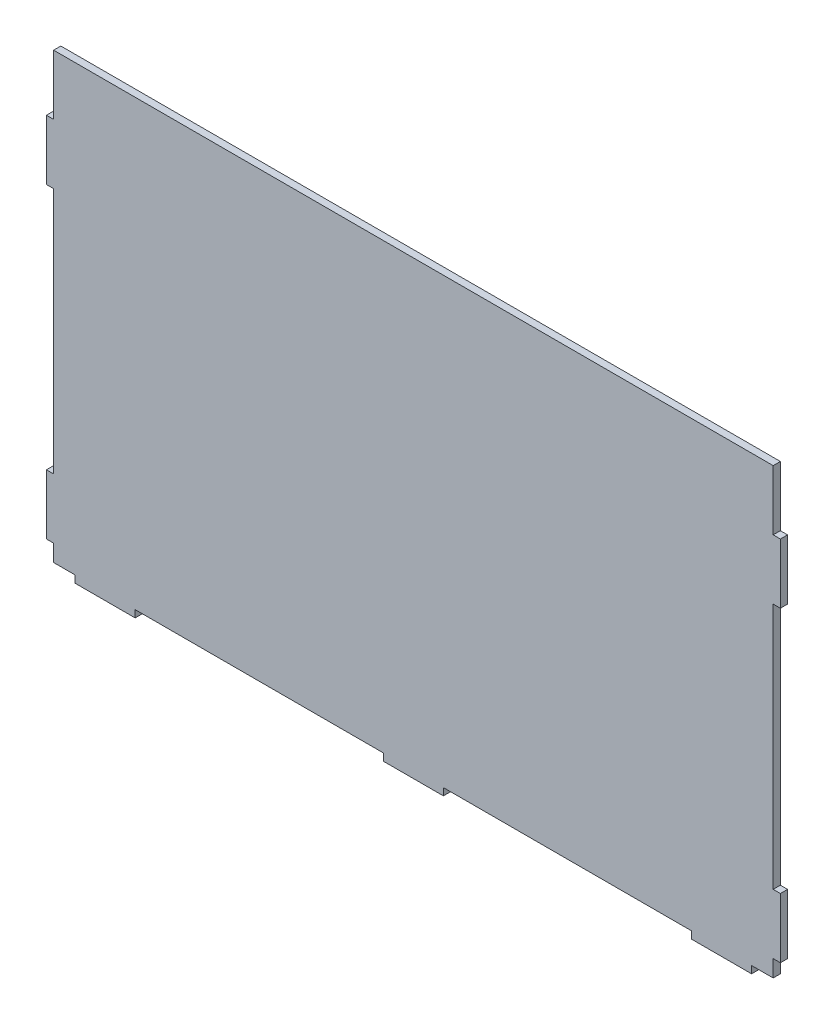
SolidWorks part; units mm, degrees
material "Maple"
ref_plane "Front Plane" through (0, 0, 0) normal (0, 0, 1) x (1, 0, 0)
ref_plane "Top Plane" through (0, 0, 0) normal (0, 1, 0) x (1, 0, 0)
ref_plane "Right Plane" through (0, 0, 0) normal (1, 0, 0) x (0, 0, -1)
sketch "Sketch1" plane through (0, 0, 0) normal (0, 0, 1) x (1, 0, 0)
  line L0 (128.9646, -1027.1029) -> (128.9646, -1021.1029)
  line L13 (146.9646, -651.1029) -> (-453.0354, -651.1029)
  line L59 (-453.0354, -651.1029) -> (-453.0354, -701.1029)
  line L60 (-453.0354, -701.1029) -> (-459.0354, -701.1029)
  line L61 (-459.0354, -701.1029) -> (-459.0354, -751.1029)
  line L62 (-459.0354, -751.1029) -> (-453.0354, -751.1029)
  line L63 (-453.0354, -751.1029) -> (-453.0354, -957.1029)
  line L64 (128.9646, -1021.1029) -> (146.9646, -1021.1029)
  line L71 (152.9646, -1007.1029) -> (152.9646, -957.1029)
  line L76 (-459.0354, -957.1029) -> (-453.0354, -957.1029)
  line L77 (-459.0354, -1007.1029) -> (-459.0354, -957.1029)
  line L78 (-453.0354, -1007.1029) -> (-459.0354, -1007.1029)
  line L79 (-453.0354, -1021.1029) -> (-453.0354, -1007.1029)
  line L81 (128.9646, -1027.1029) -> (78.9646, -1027.1029)
  line L83 (-435.0354, -1021.1029) -> (-435.0354, -1027.1029)
  line L84 (-435.0354, -1027.1029) -> (-385.0354, -1027.1029)
  line L85 (-385.0354, -1021.1029) -> (-385.0354, -1027.1029)
  line L86 (78.9646, -1021.1029) -> (-128.0354, -1021.1029)
  line L87 (-178.0354, -1021.1029) -> (-385.0354, -1021.1029)
  line L88 (78.9646, -1021.1029) -> (78.9646, -1027.1029)
  line L91 (-435.0354, -1021.1029) -> (-453.0354, -1021.1029)
  line L93 (-178.0354, -1021.1029) -> (-178.0354, -1027.1029)
  line L94 (-178.0354, -1027.1029) -> (-128.0354, -1027.1029)
  line L95 (-128.0354, -1021.1029) -> (-128.0354, -1027.1029)
  line L96 (152.9646, -957.1029) -> (146.9646, -957.1029)
  line L97 (146.9646, -751.1029) -> (146.9646, -957.1029)
  line L98 (152.9646, -751.1029) -> (146.9646, -751.1029)
  line L99 (152.9646, -701.1029) -> (152.9646, -751.1029)
  line L100 (146.9646, -701.1029) -> (152.9646, -701.1029)
  line L101 (146.9646, -651.1029) -> (146.9646, -701.1029)
  line L102 (146.9646, -1021.1029) -> (146.9646, -1007.1029)
  line L103 (146.9646, -1007.1029) -> (152.9646, -1007.1029)
  point P0 (137.9646, -1021.1029)
  point P18 (-456.0354, -751.1029)
  point P19 (146.9646, -1014.1029)
  point P21 (78.9646, -1024.1029)
  point P23 (146.1763, -615.6029)
  dimension "D2" = 50
  dimension "D3" = 6
  dimension "D4" = 50
  dimension "D5" = 6
  dimension "D6" = 14
  dimension "D7" = 50
  dimension "D8" = 18
  dimension "D9" = 50
  dimension "D10" = 50
  dimension "D11" = 370
  dimension "D12" = 50
  dimension "D13" = 6
  dimension "D14" = 14
  dimension "D15" = 50
  dimension "D16" = 600
  dimension "D17" = 370
  dimension "D18" = 600
  dimension "D19" = 600
  dimension "D20" = 6
  dimension "D21" = 6
  dimension "D22" = 6
  dimension "D23" = 90
  dimension "D24" = 6
  dimension "D25" = 6
  dimension "D26" = 6
  dimension "D27" = 6
  dimension "D28" = 18
  dimension "D29" = 370
  dimension "D30" = 370
extrude "Boss-Extrude1" add sketch "Sketch1" along normal blind 6
